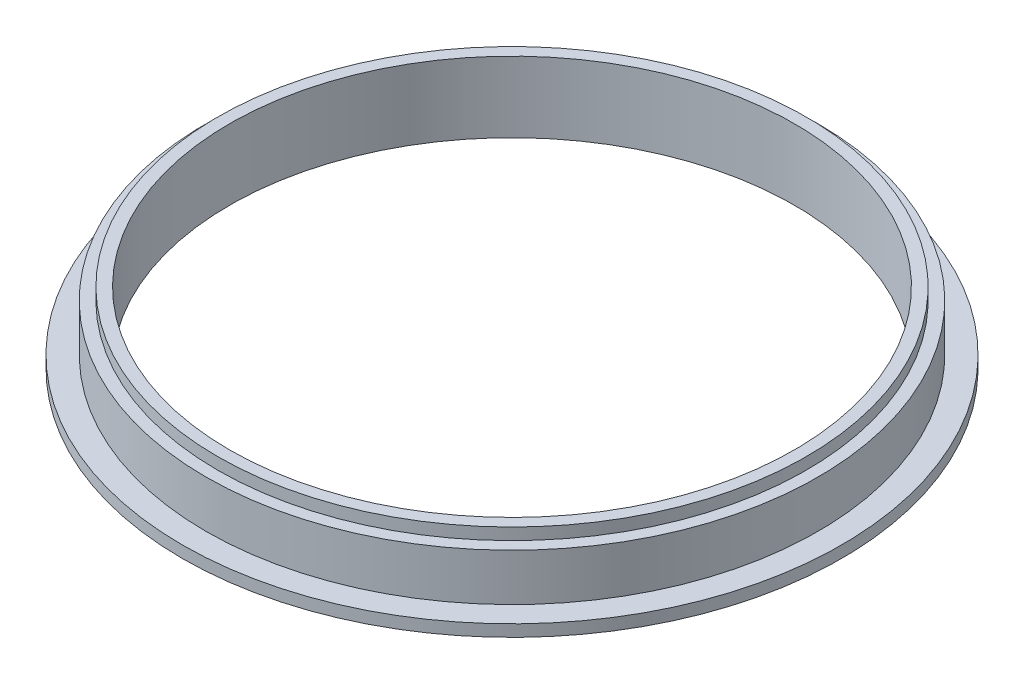
SolidWorks part; units mm, degrees
ref_plane "Plan de face" through (0, 0, 0) normal (0, 0, 1) x (1, 0, 0)
ref_plane "Plan de dessus" through (0, 0, 0) normal (0, 1, 0) x (1, 0, 0)
ref_plane "Plan de droite" through (0, 0, 0) normal (1, 0, 0) x (0, 0, -1)
sketch "Esquisse1" plane through (0, 0, 0) normal (0, 1, 0) x (1, 0, 0)
  circle A0 centre (0, 0) radius 28
  dimension "D1" = 56
extrude "Boss.-Extru.2" add sketch "Esquisse1" along normal blind 1 contours A0
sketch "Esquisse2" plane through (0, 1, 0) normal (0, 1, 0) x (1, 0, 0)
  circle A1 centre (0, 0) radius 24
  circle A2 centre (0, 0) radius 26
  circle A3 centre (0, 0) radius 26
  dimension "D1" = 2
  dimension "D2" = 2
extrude "Boss.-Extru.5" add sketch "Esquisse2" along normal blind 4
sketch "Esquisse6" plane through (0, 5, 0) normal (0, 1, 0) x (1, 0, 0)
  circle A2 centre (0, 0) radius 25
  circle A3 centre (0, 0) radius 25
  dimension "D1" = 1
extrude "Boss.-Extru.6" add sketch "Esquisse6" along normal blind 1
sketch "Esquisse7" plane through (0, 6, 0) normal (0, 1, 0) x (1, 0, 0)
  circle A2 centre (0, 0) radius 24
  circle A3 centre (0, 0) radius 24
  dimension "D1" = 1
extrude "Enlèv. mat.-Extru.2" cut sketch "Esquisse7" against normal through all
